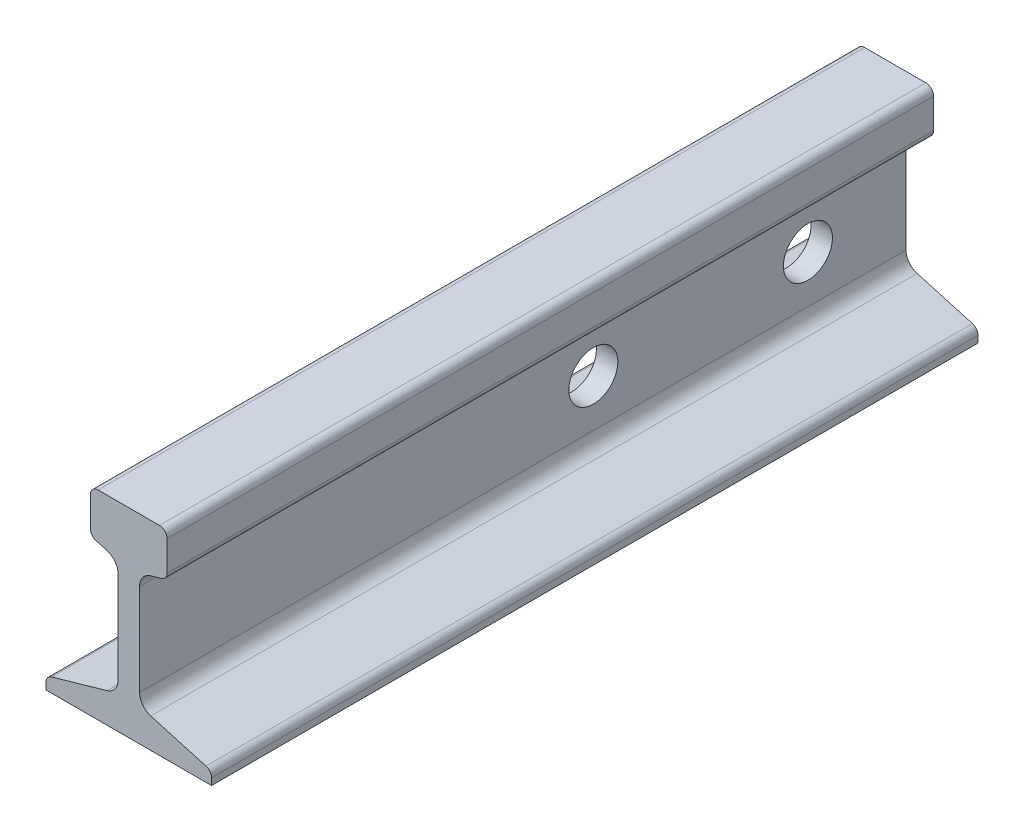
SolidWorks part; units mm, degrees
ref_plane "前视基准面" through (0, 0, 0) normal (0, 0, 1) x (1, 0, 0)
ref_plane "上视基准面" through (0, 0, 0) normal (0, 1, 0) x (1, 0, 0)
ref_plane "右视基准面" through (0, 0, 0) normal (1, 0, 0) x (0, 0, -1)
sketch "草图1" plane through (0, 0, 0) normal (0, 0, 1) x (1, 0, 0)
  line L0 (0, 0) -> (54, 0)
  line L1 (0, 0) -> (0, 2.1929)
  line L2 (27, 0) -> (27, 75.8492) construction
  line L3 (17, 65) -> (37, 65)
  line L4 (54, 2.1929) -> (54, 0)
  line L5 (23.5267, 44.5085) -> (23.5267, 14.5721)
  line L6 (30.5267, 44.5237) -> (30.5267, 14.5569)
  line L7 (14.5, 62.5) -> (14.5, 52.7448)
  line L8 (39.5, 62.5) -> (39.5, 52.7448)
  line L9 (34.1531, 49.3313) -> (37.6868, 50.341)
  line L11 (34.1531, 9.7492) -> (52.1868, 4.5967)
  line L12 (10.2906, 48) -> (45.1175, 48) construction
  line L13 (10.2906, 12) -> (45.1175, 12) construction
  line L14 (19.9003, 9.7645) -> (1.8132, 4.5967)
  line L16 (19.9003, 49.3161) -> (16.3132, 50.341)
  arc A0 (23.5267, 44.5085) -> (19.9003, 49.3161) centre (18.5267, 44.5085) ccw
  arc A1 (23.5267, 14.5721) -> (19.9003, 9.7645) centre (18.5267, 14.5721) cw
  arc A2 (34.1531, 9.7492) -> (30.5267, 14.5569) centre (35.5267, 14.5569) cw
  arc A3 (30.5267, 44.5237) -> (34.1531, 49.3313) centre (35.5267, 44.5237) cw
  arc A4 (1.8132, 4.5967) -> (0, 2.1929) centre (2.5, 2.1929) ccw
  arc A5 (54, 2.1929) -> (52.1868, 4.5967) centre (51.5, 2.1929) ccw
  arc A6 (14.5, 62.5) -> (17, 65) centre (17, 62.5) cw
  arc A7 (39.5, 62.5) -> (37, 65) centre (37, 62.5) ccw
  arc A8 (39.5, 52.7448) -> (37.6868, 50.341) centre (37, 52.7448) cw
  arc A9 (14.5, 52.7448) -> (16.3132, 50.341) centre (17, 52.7448) ccw
  point P15 (27, 48)
  point P16 (27, 12)
  point P20 (27, 48)
  point P23 (27, 48)
  point P26 (27, 12)
  point P63 (0, 4.0787)
  point P66 (54, 4.0787)
  point P69 (14.5, 65)
  point P72 (39.5, 65)
  point P74 (39.5, 50.859)
  point P77 (14.5, 50.859)
  dimension "D9" = 5
  dimension "D10" = 5
  dimension "D11" = 5
  dimension "D12" = 5
  dimension "D13" = 2.5
  dimension "D14" = 2.5
  dimension "D15" = 2.5
  dimension "D16" = 2.5
  dimension "D17" = 2.5
  dimension "D18" = 2.5
  dimension "D1" = 54
  dimension "D3" = 7
  dimension "D4" = 25
  dimension "D2" = 65
  dimension "D7" = 15.945
  dimension "D8" = 15.945
  dimension "D6" = 12
  dimension "D5" = 17
extrude "凸台-拉伸1" add sketch "草图1" along normal blind 250 contours L8 A8 L9 A3 L6 A2 L11 A5 L4 L0 L1 A4 L14 A1 L5 A0 L16 A9 L7 A6 L3 A7
sketch "草图7" plane through (0, 0, 0) normal (1, 0, 0) x (0, 0, -1)
  line L0 (12.6618, 30) -> (-187.3382, 30) construction
  line L1 (-250, 65) -> (0, 65) construction
  line L2 (0, 44.5085) -> (0, 14.5721) construction
  circle A0 centre (-32, 30) radius 8
  circle A1 centre (-102, 30) radius 8
  dimension "D4" = 16
  dimension "D1" = 35
  dimension "D2" = 32
  dimension "D3" = 70
extrude "切除-拉伸2" cut sketch "草图7" along normal blind 40 contours A0 | A1
equation "\"轨宽\"= 54mm"
equation "\"D1@草图1\"= \"轨宽\""
equation "\"轨高\"= 65mm"
equation "\"腰厚\"= 7.00mm"
equation "\"D3@草图1\"= \"腰厚\""
equation "\"头宽\"= 25mm"
equation "\"D4@草图1\"= \"头宽\""
equation "\"D\"= 17.00mm"
equation "\"F\"= 12.00mm"
equation "\"斜度\"= atn ( 1 / 3.5 )"
equation "\"D2@草图1\"= \"轨高\""
equation "\"D7@草图1\"= \"斜度\""
equation "\"D8@草图1\"= \"斜度\""
equation "\"腰部倒角\"= 5mm"
equation "\"D9@草图1\"= \"腰部倒角\""
equation "\"D10@草图1\"= \"腰部倒角\""
equation "\"D11@草图1\"= \"腰部倒角\""
equation "\"D12@草图1\"= \"腰部倒角\""
equation "\"D13@草图1\"= \"腰部倒角\" / 2"
equation "\"D14@草图1\"= \"腰部倒角\" / 2"
equation "\"D15@草图1\"= \"腰部倒角\" / 2"
equation "\"D16@草图1\"= \"腰部倒角\" / 2"
equation "\"D17@草图1\"= \"腰部倒角\" / 2"
equation "\"D18@草图1\"= \"腰部倒角\" / 2"
equation "\"h\"= 35.00mm"
equation "\"S1\"= 32.00mm"
equation "\"S2\"= 70mm"
equation "\"D1@草图7\"= \"h\""
equation "\"D2@草图7\"= \"S1\""
equation "\"D3@草图7\"= \"S2\""
equation "\"连接孔直径\"= 16mm"
equation "\"D4@草图7\"= \"连接孔直径\""
equation "\"D5@草图1\"= \"D\""
equation "\"D6@草图1\"= \"F\""
